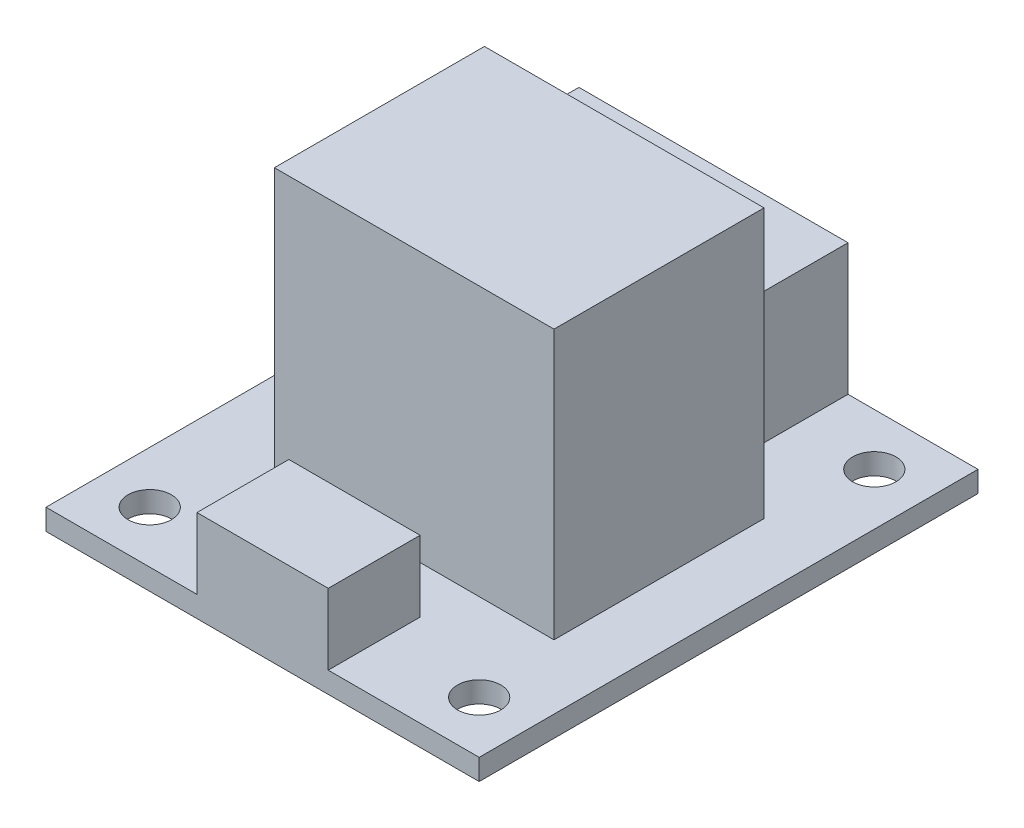
SolidWorks part; units mm, degrees
ref_plane "Front Plane" through (0, 0, 0) normal (0, 0, 1) x (1, 0, 0)
ref_plane "Top Plane" through (0, 0, 0) normal (0, 1, 0) x (1, 0, 0)
ref_plane "Right Plane" through (0, 0, 0) normal (1, 0, 0) x (0, 0, -1)
sketch "Sketch1" plane through (0, 0, 0) normal (0, 1, 0) x (1, 0, 0)
  line L1 (0, 0) -> (33, 0)
  line L2 (0, 0) -> (0, 38)
  line L3 (0, 38) -> (33, 38)
  line L4 (33, 0) -> (33, 38)
  dimension "D1" = 33
  dimension "D2" = 38
extrude "Boss-Extrude1" add sketch "Sketch1" along normal blind 1.6
sketch "Sketch2" plane through (0, 1.6, 0) normal (0, 1, 0) x (1, 0, 0)
  line L0 (29.05, 2.3) -> (29.05, 0) construction
  line L1 (33, 0) -> (29.05, 0) construction
  line L2 (33, 0) -> (33, 3.95) construction
  line L3 (33, 3.95) -> (29.05, 3.95) construction
  line L4 (29.05, 0) -> (29.05, 3.95) construction
  line L5 (16.5, 0) -> (16.5, 7.689) construction
  line L6 (0, 0) -> (33, 0) construction
  line L7 (0, 19) -> (8.654, 19) construction
  line L8 (0, 38) -> (0, 0) construction
  circle A0 centre (29.05, 3.95) radius 1.65
  circle A1 centre (3.95, 3.95) radius 1.65
  circle A2 centre (29.05, 34.05) radius 1.65
  dimension "D1" = 3.3
  dimension "D2" = 2.3
extrude "Cut-Extrude1" cut sketch "Sketch2" against normal blind 1.6
sketch "Sketch3" plane through (0, 1.6, 0) normal (0, 1, 0) x (1, 0, 0)
  line L0 (16.5, 0) -> (16.5, 8.3268) construction
  line L2 (0, 0) -> (33, 0) construction
  line L4 (21.5, 7) -> (11.5, 7)
  line L5 (21.5, 7) -> (21.5, 0)
  line L6 (21.5, 0) -> (11.5, 0)
  line L7 (11.5, 7) -> (11.5, 0)
  line L8 (21.5, 7) -> (11.5, 0) construction
  line L9 (21.5, 0) -> (11.5, 7) construction
  point P4 (16.5, 3.5)
  dimension "D1" = 7
  dimension "D2" = 10
extrude "Boss-Extrude2" add sketch "Sketch3" along normal blind 5.4
sketch "Sketch4" plane through (0, 1.6, 0) normal (0, 1, 0) x (1, 0, 0)
  line L0 (0, 38) -> (0, 0) construction
  line L1 (6.8, 26.6) -> (28.1, 26.6)
  line L2 (6.8, 26.6) -> (6.8, 10.6)
  line L3 (6.8, 10.6) -> (28.1, 10.6)
  line L4 (28.1, 26.6) -> (28.1, 10.6)
  line L5 (0, 0) -> (11.5, 0) construction
  dimension "D1" = 16
  dimension "D2" = 21.3
  dimension "D3" = 6.8
  dimension "D4" = 10.6
extrude "Boss-Extrude3" add sketch "Sketch4" along normal blind 20.5
sketch "Sketch5" plane through (0, 1.6, 0) normal (0, 1, 0) x (1, 0, 0)
  line L0 (33, 38) -> (0, 38) construction
  line L1 (2.6, 38) -> (23.1, 38)
  line L2 (2.6, 38) -> (2.6, 29.7)
  line L3 (2.6, 29.7) -> (23.1, 29.7)
  line L4 (23.1, 38) -> (23.1, 29.7)
  line L5 (0, 38) -> (0, 0) construction
  dimension "D1" = 2.6
  dimension "D2" = 8.3
  dimension "D3" = 20.5
extrude "Boss-Extrude4" add sketch "Sketch5" along normal blind 10
